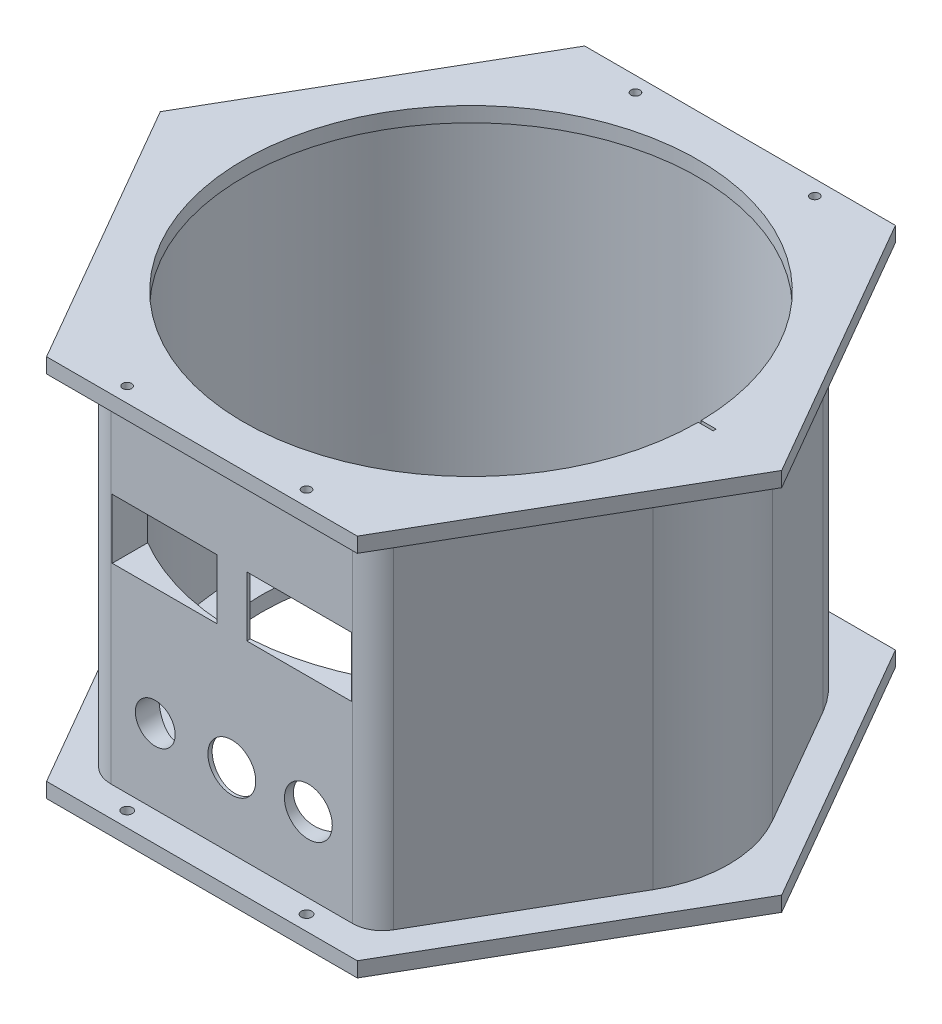
SolidWorks part; units mm, degrees
ref_plane "Front Plane" through (0, 0, 0) normal (0, 0, 1) x (1, 0, 0)
ref_plane "Top Plane" through (0, 0, 0) normal (0, 1, 0) x (1, 0, 0)
ref_plane "Right Plane" through (0, 0, 0) normal (1, 0, 0) x (0, 0, -1)
sketch "Sketch1" plane through (0, 0, 0) normal (0, 1, 0) x (1, 0, 0)
  line L7 (92.376, 0) -> (46.188, 80)
  line L8 (46.188, 80) -> (-46.188, 80)
  line L9 (-46.188, 80) -> (-92.376, 0)
  line L10 (-92.376, 0) -> (-46.188, -80)
  line L11 (-46.188, -80) -> (46.188, -80)
  line L12 (46.188, -80) -> (92.376, 0)
  arc A1 (-27.8388, 75) -> (-51.0325, -61.6091) centre (0, 0) ccw construction
  circle A2 centre (0, 0) radius 79
  arc A3 (51.0325, 61.6091) -> (25.2107, 75.9238) centre (0, 0) ccw construction
  arc A4 (78.8713, 13.3909) -> (69.282, 40) centre (0, 0) ccw construction
  arc A5 (-27.8388, -75) -> (53.001, -59.9241) centre (0, 0) ccw construction
  dimension "D3" = 158
  dimension "D2" = 160
extrude "Boss-Extrude1" add sketch "Sketch1" along normal blind 123
sketch "Sketch2" plane through (0, 0, 0) normal (0, -1, 0) x (1, 0, 0)
  line L1 (103.923, 0) -> (51.9615, 90)
  line L2 (51.9615, 90) -> (-51.9615, 90)
  line L3 (-51.9615, 90) -> (-103.923, 0)
  line L4 (-103.923, 0) -> (-51.9615, -90)
  line L5 (-51.9615, -90) -> (51.9615, -90)
  line L6 (51.9615, -90) -> (103.923, 0)
  circle A0 centre (0, 0) radius 70
  circle A2 centre (0, 0) radius 90 construction
  dimension "D1" = 140
  dimension "D2" = 180
extrude "Boss-Extrude2" add sketch "Sketch2" against normal blind 5
sketch "Sketch3" plane through (0, 123, 0) normal (0, 1, 0) x (1, 0, 0)
  line L1 (103.923, 0) -> (51.9615, 90)
  line L2 (51.9615, 90) -> (-51.9615, 90)
  line L3 (-51.9615, 90) -> (-103.923, 0)
  line L4 (-103.923, 0) -> (-51.9615, -90)
  line L5 (-51.9615, -90) -> (51.9615, -90)
  line L6 (51.9615, -90) -> (103.923, 0)
  circle A0 centre (0, 0) radius 76
  arc A1 (28.5424, 85.3542) -> (-28.5424, 85.3542) centre (0, 0) ccw construction
  circle A2 centre (30, 85) radius 1.5
  circle A3 centre (-30, 85) radius 1.5
  circle A4 centre (30, -85) radius 1.5
  circle A5 centre (-30, -85) radius 1.5
  arc A6 (-31.357, 84.3608) -> (-31.357, -84.3608) centre (0, 0) ccw construction
  arc A7 (-28.5424, -85.3542) -> (28.5424, -85.3542) centre (0, 0) ccw construction
  arc A8 (31.357, -84.3608) -> (31.357, 84.3608) centre (0, 0) ccw construction
  dimension "D1" = 152
  dimension "D6" = 3
  dimension "D7" = 3
  dimension "D11" = 3
  dimension "D12" = 3
  dimension "D2" = 180
  dimension "D3" = 85
  dimension "D4" = 30
extrude "Boss-Extrude3" add sketch "Sketch3" along normal blind 5
sketch "Sketch8" plane through (0, 0, 80) normal (0, 0, 1) x (1, 0, 0)
  line L2 (5, 89.1519) -> (40, 89.1519)
  line L3 (40, 89.1519) -> (40, 69.1519)
  line L4 (40, 69.1519) -> (5, 69.1519)
  line L5 (5, 69.1519) -> (5, 89.1519)
  line L7 (-5, 89.1519) -> (-40, 89.1519)
  line L8 (-40, 89.1519) -> (-40, 69.1519)
  line L9 (-40, 69.1519) -> (-5, 69.1519)
  line L10 (-5, 69.1519) -> (-5, 89.1519)
  dimension "D3" = 35
  dimension "D4" = 35
  dimension "D5" = 20
extrude "Cut-Extrude1" cut sketch "Sketch8" against normal blind 20
fillet "Fillet3" radius 10 2 edges at (46.188, 61.5, 80) (-46.188, 61.5, 80)
fillet "Fillet4" radius 40 4 edges at (-92.376, 61.5, 0) (-46.188, 61.5, -80) (46.188, 61.5, -80) (92.376, 61.5, 0)
sketch "Sketch12" plane through (0, 0, 0) normal (0, -1, 0) x (1, 0, 0)
  line L0 (0, 90) -> (0, 85)
  line L1 (51.9615, 90) -> (-51.9615, 90) construction
  line L2 (0, 85) -> (30, 85)
  line L3 (0, 85) -> (-30, 85)
  line L4 (0, -90) -> (0, -85)
  line L5 (-51.9615, -90) -> (51.9615, -90) construction
  line L6 (0, -85) -> (-30, -85)
  line L7 (0, -85) -> (30, -85)
  circle A0 centre (-30, 85) radius 1.75
  circle A1 centre (30, 85) radius 1.75
  circle A2 centre (30, -85) radius 1.75
  circle A3 centre (-30, -85) radius 1.75
  dimension "D4" = 3.5
  dimension "D5" = 3.5
  dimension "D9" = 3.5
  dimension "D10" = 3.5
  dimension "D1" = 5
  dimension "D2" = 30
  dimension "D3" = 30
  dimension "D6" = 5
  dimension "D7" = 30
  dimension "D8" = 30
extrude "Cut-Extrude3" cut sketch "Sketch12" against normal blind 10
sketch "Sketch16" plane through (0, 128, 0) normal (0, 1, 0) x (1, 0, 0)
  line L0 (0, 0) -> (81, 0)
  line L1 (81, 0) -> (81, 1)
  line L2 (81, 1) -> (-81, 1)
  line L3 (-81, 1) -> (-81, 0)
  line L4 (-81, 0) -> (-81, -1)
  line L5 (-81, -1) -> (81, -1)
  line L6 (81, -1) -> (81, 0)
  circle M15 centre (0, 0) radius 76
  dimension "D1" = 81
  dimension "D2" = 162
  dimension "D3" = 1
  dimension "D4" = 1
  dimension "D5" = 1
  dimension "D6" = 162
extrude "Cut-Extrude4" cut sketch "Sketch16" against normal blind 10 contours L1 L2 L0 M15
sketch "Sketch20" plane through (0, 0, 80) normal (0, 0, 1) x (1, 0, 0)
  line L0 (0, 5) -> (0, 30)
  line L1 (51.9615, 5) -> (-51.9615, 5) construction
  line L2 (0, 30) -> (-25.6, 30)
  line L3 (0, 30) -> (25.6, 30)
  circle A0 centre (-25.6, 30) radius 6.65
  circle A1 centre (0, 30) radius 8
  circle A2 centre (25.6, 30) radius 8
  dimension "D4" = 13.3
  dimension "D5" = 16
  dimension "D6" = 16
  dimension "D1" = 25.6
  dimension "D2" = 25.6
  dimension "D3" = 25
extrude "Cut-Extrude7" cut sketch "Sketch20" against normal blind 22
